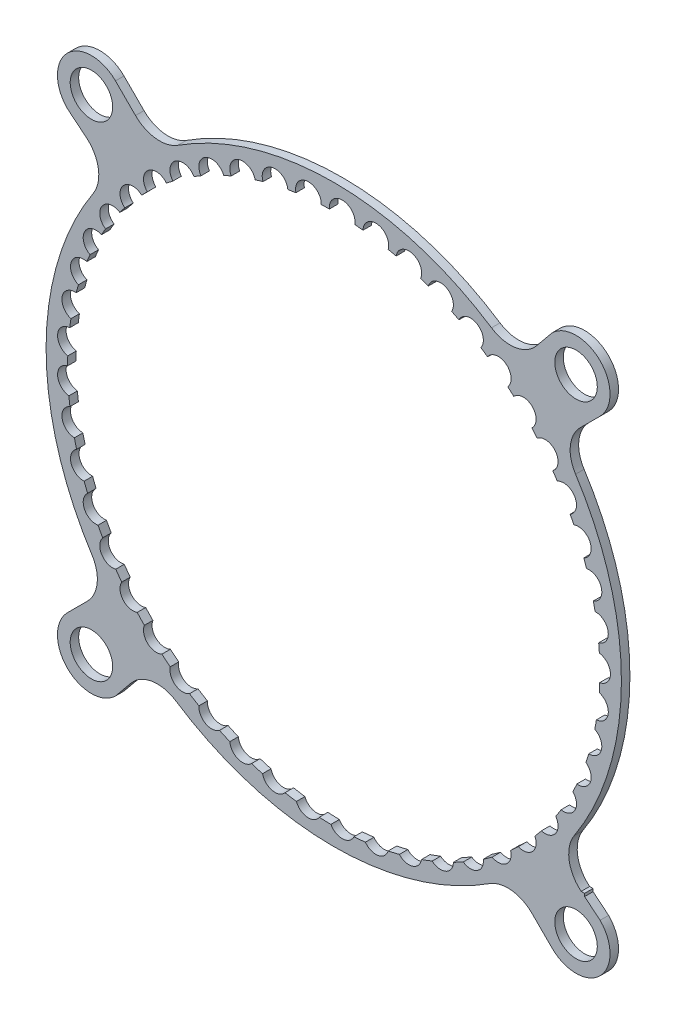
SolidWorks part; units mm, degrees
ref_plane "前视基准面" through (0, 0, 0) normal (0, 0, 1) x (1, 0, 0)
ref_plane "上视基准面" through (0, 0, 0) normal (0, 1, 0) x (1, 0, 0)
ref_plane "右视基准面" through (0, 0, 0) normal (1, 0, 0) x (0, 0, -1)
sketch "草图1" plane through (0, 0, 0) normal (0, 0, 1) x (1, 0, 0)
  line L0 (0, 0.4371) -> (23.55, 0.4371) construction
  line L130 (29.1007, -23.4089) -> (29.5023, -23.4089)
  line L136 (29.5023, -23.4089) -> (29.5023, -23.738)
  line L137 (29.5023, -23.738) -> (31.3282, -25.2342)
  line L139 (28.4997, -28.0626) -> (34.1987, -22.3636) construction
  line L140 (28.4997, -28.0626) -> (24.8719, -31.6905) construction
  line L143 (25.6713, -30.891) -> (23.3201, -28.5398)
  line L144 (-31.3282, -25.2342) -> (-28.9769, -22.8829)
  line L145 (-25.6713, -30.891) -> (-23.8461, -28.6636)
  line L146 (-25.6713, 31.7653) -> (-23.3201, 29.4141)
  line L147 (-31.3282, 26.1085) -> (-29.1007, 24.2832)
  line L148 (31.3282, 26.1085) -> (28.9769, 23.7572)
  line L151 (23.55, 0.4371) -> (23.55, -23.1129) construction
  line L152 (0, 0.4371) -> (23.55, -23.1129) construction
  line L153 (23.55, -23.1129) -> (28.4997, -28.0626) construction
  line L154 (25.6713, 31.7653) -> (23.8461, 29.5379)
  circle A2 centre (16.0883, -26.1022) radius 1.51
  circle A3 centre (12.5625, -27.9417) radius 1.51
  circle A4 centre (8.8303, -29.3151) radius 1.51
  circle A5 centre (4.9532, -30.2) radius 1.51
  circle A6 centre (0.9947, -30.5819) radius 1.51
  circle A7 centre (-2.9801, -30.4544) radius 1.51
  circle A8 centre (-6.9059, -29.8197) radius 1.51
  circle A9 centre (19.35, -23.827) radius 1.51
  circle A10 centre (-10.7184, -28.6882) radius 1.51
  circle A11 centre (-14.3549, -27.0785) radius 1.51
  circle A12 centre (-17.7556, -25.0169) radius 1.51
  circle A13 centre (-20.8649, -22.5374) radius 1.51
  circle A14 centre (-23.6315, -19.6806) radius 1.51
  circle A15 centre (-26.0101, -16.4935) radius 1.51
  circle A16 centre (-27.9616, -13.0284) radius 1.51
  circle A17 centre (-29.4539, -9.3422) radius 1.51
  circle A18 centre (-30.4627, -5.4955) radius 1.51
  circle A19 centre (-30.9712, -1.5513) radius 1.51
  circle A20 centre (-30.9712, 2.4256) radius 1.51
  circle A21 centre (-30.4627, 6.3698) radius 1.51
  circle A22 centre (-29.4539, 10.2165) radius 1.51
  circle A23 centre (-27.9616, 13.9027) radius 1.51
  circle A24 centre (-26.0101, 17.3678) radius 1.51
  circle A25 centre (-23.6315, 20.5549) radius 1.51
  circle A26 centre (-20.8649, 23.4117) radius 1.51
  circle A27 centre (-17.7556, 25.8912) radius 1.51
  circle A28 centre (-14.3549, 27.9528) radius 1.51
  circle A29 centre (-10.7184, 29.5625) radius 1.51
  circle A30 centre (-6.9059, 30.694) radius 1.51
  circle A31 centre (-2.9801, 31.3287) radius 1.51
  circle A32 centre (0.9947, 31.4562) radius 1.51
  circle A33 centre (4.9532, 31.0743) radius 1.51
  circle A34 centre (8.8303, 30.1894) radius 1.51
  circle A35 centre (12.5625, 28.8159) radius 1.51
  circle A36 centre (16.0883, 26.9765) radius 1.51
  circle A37 centre (19.35, 24.7013) radius 1.51
  circle A38 centre (22.294, 22.0277) radius 1.51
  circle A39 centre (24.8719, 18.9995) radius 1.51
  circle A40 centre (27.0414, 15.6666) radius 1.51
  circle A41 centre (28.7669, 12.0836) radius 1.51
  circle A42 centre (30.02, 8.3093) radius 1.51
  circle A43 centre (30.7802, 4.4058) radius 1.51
  circle A44 centre (31.035, 0.4371) radius 1.51
  circle A45 centre (30.7802, -3.5315) radius 1.51
  circle A46 centre (30.02, -7.435) radius 1.51
  circle A47 centre (28.7669, -11.2093) radius 1.51
  circle A48 centre (27.0414, -14.7923) radius 1.51
  circle A49 centre (24.8719, -18.1252) radius 1.51
  circle A50 centre (22.294, -21.1534) radius 1.51
  circle A172 centre (0, 0.4371) radius 26.5
  arc A184 (-28.9769, -22.8829) -> (-28.4428, -17.8881) centre (-31.8053, -20.0545) ccw
  arc A185 (-28.2914, 18.9953) -> (-29.1007, 24.2832) centre (-31.636, 21.1893) ccw
  circle A187 centre (0, 0.4371) radius 33.835 construction
  circle A189 centre (28.4997, -28.0626) radius 2.5
  circle A192 centre (28.4997, -28.0626) radius 4 construction
  arc A193 (25.6713, -30.891) -> (31.3282, -25.2342) centre (28.4997, -28.0626) ccw
  circle A194 centre (-28.4997, -28.0626) radius 2.5
  arc A195 (-31.3282, -25.2342) -> (-25.6713, -30.891) centre (-28.4997, -28.0626) ccw
  circle A196 centre (-28.4997, 28.9369) radius 2.5
  arc A197 (-25.6713, 31.7653) -> (-31.3282, 26.1085) centre (-28.4997, 28.9369) ccw
  circle A198 centre (28.4997, 28.9369) radius 2.5
  arc A199 (31.3282, 26.1085) -> (25.6713, 31.7653) centre (28.4997, 28.9369) ccw
  arc A200 (-18.5582, -27.8542) -> (18.3252, -28.0057) centre (0, 0.4371) ccw
  arc A201 (-28.4428, -17.8881) -> (-28.2914, 18.9953) centre (0, 0.4371) cw
  arc A202 (-18.3252, 28.88) -> (18.5582, 28.7285) centre (0, 0.4371) cw
  arc A203 (28.4428, 18.7624) -> (28.2914, -18.121) centre (0, 0.4371) cw
  arc A204 (-23.3201, 29.4141) -> (-18.3252, 28.88) centre (-20.4916, 32.2425) ccw
  arc A205 (18.5582, 28.7285) -> (23.8461, 29.5379) centre (20.7521, 32.0731) ccw
  arc A206 (28.4428, 18.7624) -> (28.9769, 23.7572) centre (31.8053, 20.9288) cw
  arc A207 (28.2914, -18.121) -> (29.1007, -23.4089) centre (31.636, -20.315) ccw
  arc A208 (23.3201, -28.5398) -> (18.3252, -28.0057) centre (20.4916, -31.3682) ccw
  arc A209 (-18.5582, -27.8542) -> (-23.8461, -28.6636) centre (-20.7521, -31.1988) ccw
  point P149 (26.1708, -21.0081)
  point P152 (20.9288, -26.1485)
  dimension "D1" = 49
  dimension "D3" = 4
  dimension "D2" = 4
extrude "凸台-拉伸1" add sketch "草图1" along normal blind 1
sketch "草图2" plane through (0, 0, 1) normal (0, 0, 1) x (1, 0, 0)
  circle A0 centre (0, 0) radius 31.3
extrude "切除-拉伸1" cut sketch "草图2" against normal blind 1
